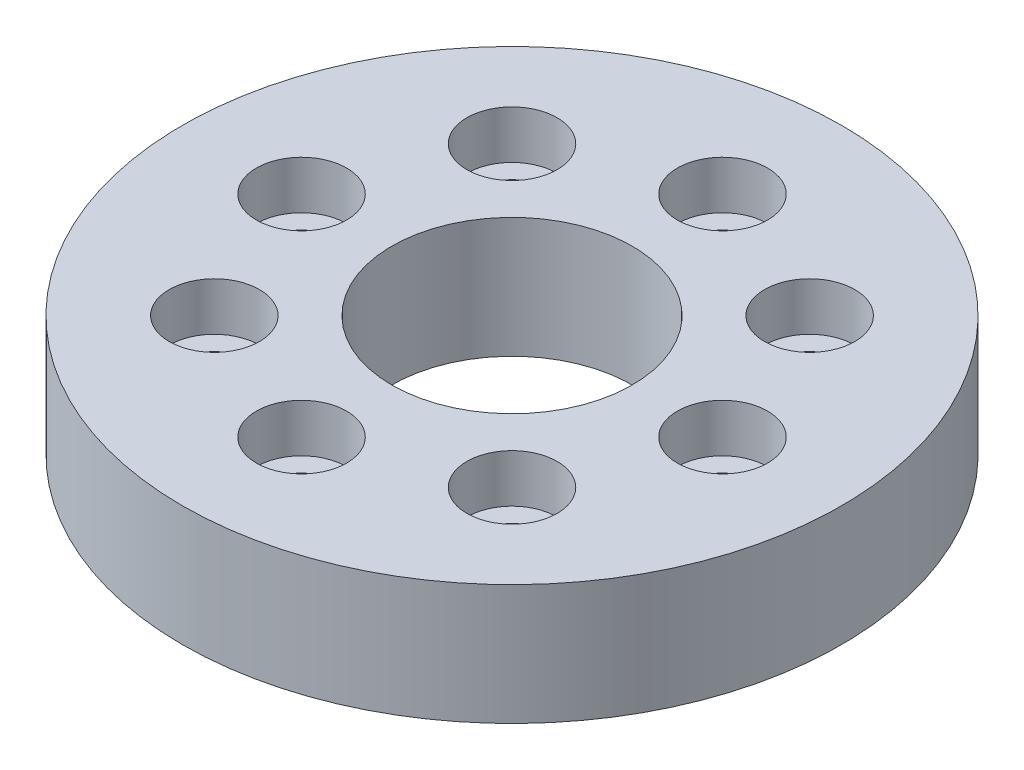
SolidWorks part; units mm, degrees
ref_plane "Front Plane" through (0, 0, 0) normal (0, 0, 1) x (1, 0, 0)
ref_plane "Top Plane" through (0, 0, 0) normal (0, 1, 0) x (1, 0, 0)
ref_plane "Right Plane" through (0, 0, 0) normal (1, 0, 0) x (0, 0, -1)
sketch "Sketch1" plane through (0, 0, 0) normal (0, 1, 0) x (1, 0, 0)
  line L0 (0, 10) -> (0, 25) construction
  circle A0 centre (0, 0) radius 10
  circle A1 centre (0, 0) radius 27.4
  circle A2 centre (0, 0) radius 25
  circle A3 centre (0, 17.5) radius 2
  circle A4 centre (12.3744, 12.3744) radius 2
  circle A5 centre (17.5, 0) radius 2
  circle A6 centre (12.3744, -12.3744) radius 2
  circle A7 centre (0, -17.5) radius 2
  circle A8 centre (-12.3744, -12.3744) radius 2
  circle A9 centre (-17.5, 0) radius 2
  circle A10 centre (-12.3744, 12.3744) radius 2
  point P26 (0, 0)
  dimension "D1" = 20
  dimension "D2" = 54.8
  dimension "D3" = 50
  dimension "D4" = 4
  dimension "D5" = 8
extrude "Boss-Extrude1" add sketch "Sketch1" along normal blind 10
sketch "Sketch2" plane through (0, 10, 0) normal (0, 1, 0) x (1, 0, 0)
  circle A0 centre (-12.3744, 12.3744) radius 3.75
  circle A1 centre (0, 17.5) radius 3.75
  circle A2 centre (12.3744, 12.3744) radius 3.75
  circle A3 centre (17.5, 0) radius 3.75
  circle A4 centre (12.3744, -12.3744) radius 3.75
  circle A5 centre (0, -17.5) radius 3.75
  circle A6 centre (-12.3744, -12.3744) radius 3.75
  circle A7 centre (-17.5, 0) radius 3.75
  point P20 (0, 0)
  dimension "D1" = 7.5
  dimension "D2" = 8
extrude "Cut-Extrude1" cut sketch "Sketch2" against normal blind 4
